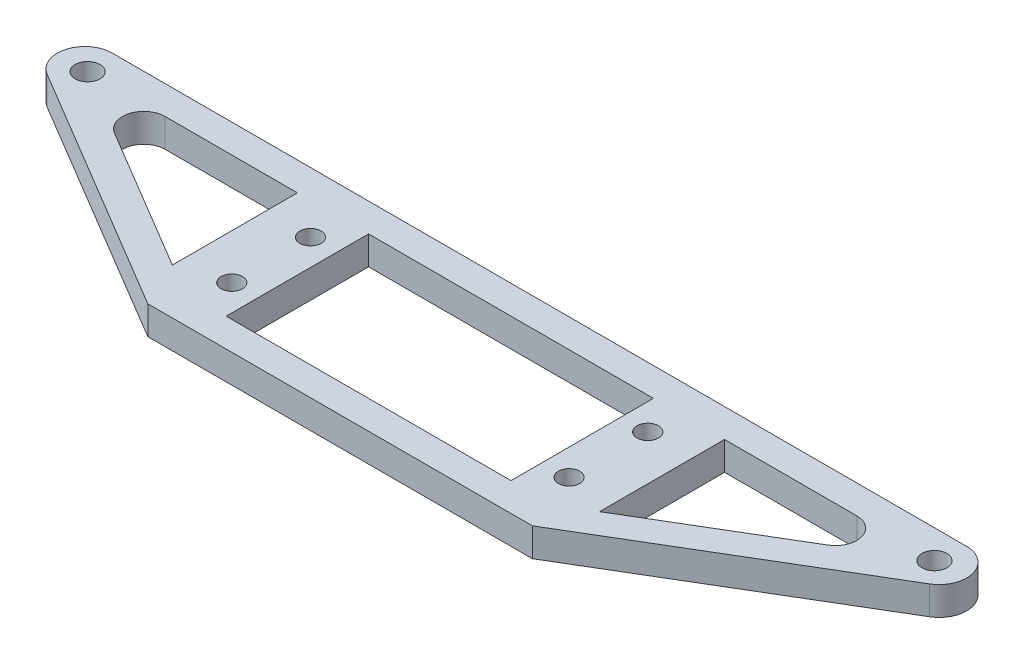
SolidWorks part; units mm, degrees
ref_plane "前视基准面" through (0, 0, 0) normal (0, 0, 1) x (1, 0, 0)
ref_plane "上视基准面" through (0, 0, 0) normal (0, 1, 0) x (1, 0, 0)
ref_plane "右视基准面" through (0, 0, 0) normal (1, 0, 0) x (0, 0, -1)
other "Configuration Table"
sketch "草图1" plane through (0, 0, 0) normal (0, 1, 0) x (1, 0, 0)
  line L0 (0, -14) -> (0, 15.0791) construction
  line L1 (-27, -14) -> (27, -14)
  line L3 (-27, 14) -> (27, 14)
  line L5 (-27, -14) -> (27, 14) construction
  line L6 (-27, 14) -> (27, -14) construction
  line L7 (-20, -10) -> (20, -10)
  line L8 (-20, -10) -> (-20, 10)
  line L9 (-20, 10) -> (20, 10)
  line L10 (20, -10) -> (20, 10)
  line L11 (-20, -10) -> (20, 10) construction
  line L12 (-20, 10) -> (20, -10) construction
  line L13 (0, 0) -> (-34.5622, 0) construction
  line L14 (27, 14) -> (60, 14)
  line L15 (27, -14) -> (61.9721, 6.8372)
  line L16 (27, 14) -> (27, -14) construction
  line L17 (30, 10) -> (59.4656, 10)
  line L18 (59.4656, 10) -> (30, -7.5563)
  line L19 (30, -7.5563) -> (30, 10)
  line L20 (-59.4656, 10) -> (-30, -7.5563)
  line L21 (-30, 10) -> (-59.4656, 10)
  line L22 (-27, -14) -> (-61.9721, 6.8372)
  line L23 (-27, 14) -> (-60, 14)
  line L24 (-30, -7.5563) -> (-30, 10)
  circle A0 centre (-23.681, 5.5295) radius 1.5
  circle A1 centre (-23.681, -5.5295) radius 1.5
  circle A2 centre (23.681, -5.5295) radius 1.5
  circle A3 centre (23.681, 5.5295) radius 1.5
  arc A4 (61.9721, 6.8372) -> (60, 14) centre (60, 10.1471) ccw
  arc A5 (-61.9721, 6.8372) -> (-60, 14) centre (-60, 10.1471) cw
  point P0 (0, 0)
  point P6 (0, 0)
  dimension "D5" = 3
  dimension "D8" = 120
  dimension "D1" = 28
  dimension "D2" = 54
  dimension "D3" = 20
  dimension "D4" = 40
  dimension "D6" = 4
  dimension "D7" = 4
  dimension "D9" = 3
extrude "凸台-拉伸1" add sketch "草图1" along normal blind 4
fillet "圆角1" radius 3 1 edges at (59.4656, 2, -10)
fillet "圆角2" radius 3 1 edges at (-59.4656, 2, -10)
ref_plane "基准面1" through (0, 10, 0) normal (0, 1, 0) x (1, 0, 0)
sketch "草图2" plane through (0, 10, 0) normal (0, 1, 0) x (1, 0, 0)
  line L3 (59.4656, 10) -> (30, 10)
  line L4 (-20, -10) -> (20, -10)
  line L5 (20, -10) -> (20, 10)
  line L6 (20, 10) -> (-20, 10)
  line L7 (-20, 10) -> (-20, -10)
  line L8 (-20, -10) -> (20, -10)
  line L9 (20, -10) -> (20, 10)
  line L10 (20, 10) -> (-20, 10)
  line L11 (-20, 10) -> (-20, -10)
  line L12 (30, -7.5563) -> (59.4656, 10)
  line L13 (30, 10) -> (30, -7.5563)
  line L14 (59.4656, 10) -> (30, 10)
  line L15 (30, -7.5563) -> (59.4656, 10)
  line L16 (30, 10) -> (30, -7.5563)
  line L17 (-59.4656, 10) -> (-30, -7.5563)
  line L18 (-30, -7.5563) -> (-30, 10)
  line L19 (-30, 10) -> (-59.4656, 10)
  line L20 (60, 14) -> (27, 14)
  line L21 (27, 14) -> (-27, 14)
  line L22 (-27, 14) -> (-60, 14)
  line L23 (-61.9721, 6.8372) -> (-27, -14)
  line L24 (-27, -14) -> (27, -14)
  line L25 (27, -14) -> (61.9721, 6.8372)
  line L26 (60, 14) -> (27, 14)
  line L27 (27, 14) -> (-27, 14)
  line L28 (-27, 14) -> (-60, 14)
  line L29 (-61.9721, 6.8372) -> (-27, -14)
  line L30 (-27, -14) -> (27, -14)
  line L31 (27, -14) -> (61.9721, 6.8372)
  line L32 (-59.4656, 10) -> (-30, -7.5563)
  line L33 (-30, -7.5563) -> (-30, 10)
  line L34 (-30, 10) -> (-59.4656, 10)
  circle A0 centre (-59.4656, 10) radius 1.75
  circle A1 centre (-23.681, 5.5295) radius 1.5
  circle A2 centre (-23.681, 5.5295) radius 1.5
  circle A3 centre (23.681, 5.5295) radius 1.5
  circle A4 centre (23.681, 5.5295) radius 1.5
  circle A5 centre (23.681, -5.5295) radius 1.5
  circle A6 centre (23.681, -5.5295) radius 1.5
  circle A7 centre (-23.681, -5.5295) radius 1.5
  circle A8 centre (-23.681, -5.5295) radius 1.5
  circle A9 centre (59.4656, 10) radius 1.75
  arc A10 (-60, 14) -> (-61.9721, 6.8372) centre (-60, 10.1471) ccw
  arc A11 (61.9721, 6.8372) -> (60, 14) centre (60, 10.1471) ccw
  arc A12 (-60, 14) -> (-61.9721, 6.8372) centre (-60, 10.1471) ccw
  arc A13 (61.9721, 6.8372) -> (60, 14) centre (60, 10.1471) ccw
  dimension "D9" = 3.5
  dimension "D10" = 3.5
  dimension "D1" = 0
  dimension "D2" = 0
  dimension "D3" = 0
  dimension "D4" = 0
  dimension "D5" = 0
  dimension "D6" = 0
  dimension "D7" = 0
  dimension "D8" = 0
extrude "切除-拉伸1" cut sketch "草图2" against normal through all contours A0 | A9
